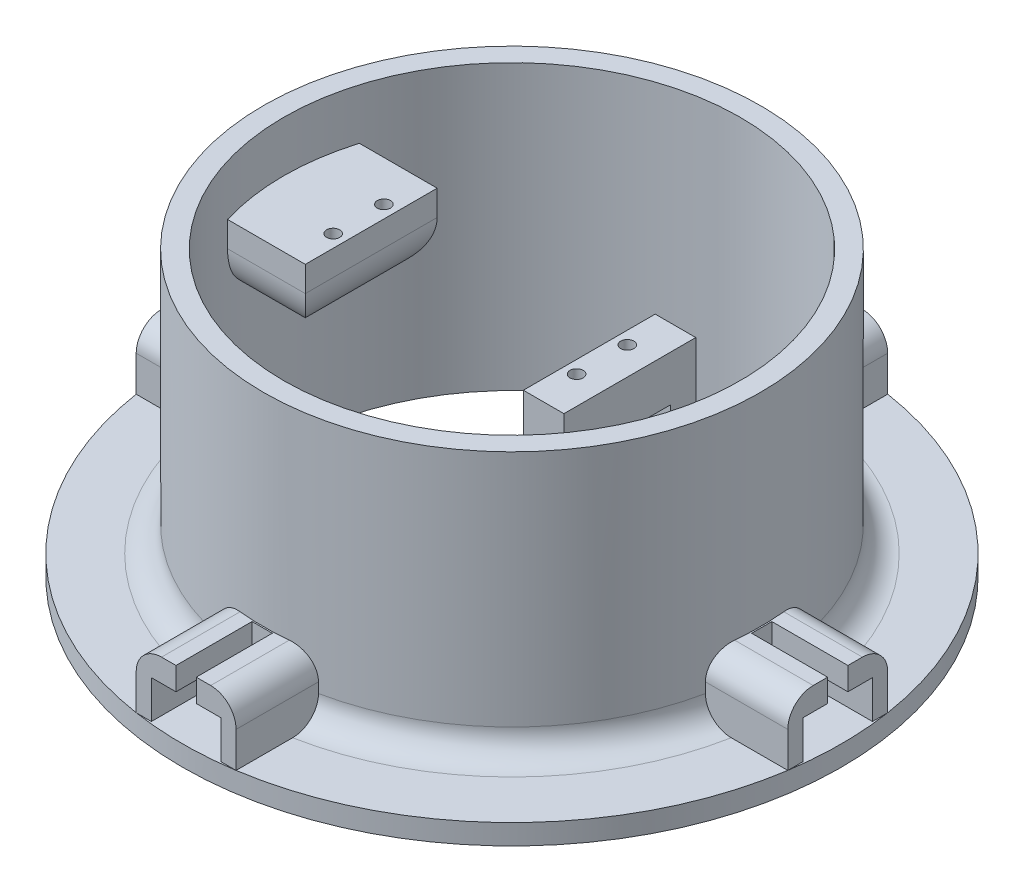
SolidWorks part; units mm, degrees
ref_plane "Alzado" through (0, 0, 0) normal (0, 0, 1) x (1, 0, 0)
ref_plane "Planta" through (0, 0, 0) normal (0, 1, 0) x (1, 0, 0)
ref_plane "Vista lateral" through (0, 0, 0) normal (1, 0, 0) x (0, 0, -1)
sketch "Croquis1" plane through (0, 0, 0) normal (0, 1, 0) x (1, 0, 0)
  circle A0 centre (0, 0) radius 45
  circle A1 centre (0, 0) radius 49
  dimension "D1" = 98
  dimension "D2" = 90
extrude "Saliente-Extruir1" add sketch "Croquis1" along normal blind 56
sketch "Croquis3" plane through (0, 0, 0) normal (0, 1, 0) x (1, 0, 0)
  circle A0 centre (0, 0) radius 49
  circle A1 centre (0, 0) radius 65
  dimension "D1" = 98
  dimension "D2" = 130
extrude "Saliente-Extruir2" add sketch "Croquis3" along normal blind 4
fillet "Redondeo1" radius 5 1 edges at (0, 4, 49)
sketch "Croquis4" plane through (0, 0, 0) normal (0, 1, 0) x (1, 0, 0)
  line L0 (45, 0) -> (19.25, 0) construction
  line L2 (15.25, -13) -> (23.25, -13)
  line L3 (15.25, -13) -> (15.25, 13)
  line L4 (15.25, 13) -> (23.25, 13)
  line L5 (23.25, -13) -> (23.25, 13)
  line L6 (15.25, -13) -> (23.25, 13) construction
  line L7 (15.25, 13) -> (23.25, -13) construction
  circle A0 centre (0, 0) radius 45 construction
  dimension "D1" = 25.75
  dimension "D2" = 8
  dimension "D3" = 26
extrude "Saliente-Extruir3" add sketch "Croquis4" along normal blind 46 separate body
sketch "Croquis5" plane through (0, 0, 0) normal (0, 1, 0) x (1, 0, 0)
  line L0 (15.25, 13) -> (32.7495, 30.8621)
  line L1 (0, 0) -> (45, 0) construction
  line L2 (38.8166, 22.7655) -> (27.25, 10.9592)
  line L3 (27.25, 10.9592) -> (27.25, -10.9592)
  line L4 (23.25, -13) -> (23.25, 13) construction
  line L5 (15.25, -13) -> (32.7495, -30.8621)
  line L6 (38.8166, -22.7655) -> (27.25, -10.9592)
  line L7 (15.25, -13) -> (23.25, -13) construction
  line L8 (23.25, 13) -> (15.25, 13) construction
  line L9 (15.25, -13) -> (23.25, -13)
  line L10 (23.25, -13) -> (23.25, 13)
  line L11 (23.25, 13) -> (15.25, 13)
  circle A0 centre (0, 0) radius 45 construction
  arc A1 (32.7495, -30.8621) -> (38.8166, -22.7655) centre (0, 0) ccw
  arc A2 (38.8166, 22.7655) -> (32.7495, 30.8621) centre (0, 0) ccw
  point P17 (27.25, 0)
  dimension "D1" = 4
  dimension "D2" = 10
extrude "Saliente-Extruir4" add sketch "Croquis5" along normal blind 2.2
sketch "Croquis6" plane through (0, 46, 0) normal (0, 1, 0) x (1, 0, 0)
  line L0 (15.25, 13) -> (-27.75, 13) construction
  line L1 (-27.75, 13) -> (-27.75, 0) construction
  line L2 (-27.75, 0) -> (-30.25, 0) construction
  line L3 (-30.25, 0) -> (-30.25, 5) construction
  line L5 (-27.75, 13) -> (-43.0813, 13)
  line L6 (-27.75, 13) -> (-27.75, -13)
  line L7 (-27.75, -13) -> (-43.0813, -13)
  circle A0 centre (0, 0) radius 45 construction
  arc A1 (-43.0813, 13) -> (-43.0813, -13) centre (0, 0) ccw
  dimension "D1" = 43
  dimension "D2" = 2.5
  dimension "D3" = 5
  dimension "D4" = 26
extrude "Saliente-Extruir5" add sketch "Croquis6" against normal blind 15
fillet "Redondeo2" radius 10 3 edges at (-35.4157, 31, -13) (-35.4157, 31, 13) (-27.75, 31, 0)
sketch "Croquis7" plane through (0, 46, 0) normal (0, 1, 0) x (1, 0, 0)
  line L0 (17.75, 0) -> (17.75, 5) construction
  line L2 (17.75, 0) -> (15.25, 0) construction
  line L3 (15.25, 13) -> (15.25, -13) construction
  line L4 (15.25, 0) -> (-30.25, 0) construction
  line L5 (-27.75, -13) -> (-27.75, 13) construction
  line L6 (-30.25, 0) -> (-30.25, -2.7854) construction
  line L7 (-30.25, -2.7854) -> (17.75, -2.7854) construction
  line L8 (-6.25, -2.7854) -> (-6.25, 3.2559) construction
  circle A0 centre (17.75, 5) radius 1.3
  circle A1 centre (17.75, -5) radius 1.3
  circle A2 centre (-30.25, -5) radius 1.3
  circle A3 centre (-30.25, 5) radius 1.3
  dimension "D4" = 2.6
  dimension "D1" = 2.5
  dimension "D2" = 2.5
  dimension "D3" = 5
  dimension "D5" = 5
extrude "Cortar-Extruir1" cut sketch "Croquis7" against normal blind 7.2
ref_plane "Plano1" through (15.25, 0, 0) normal (-1, 0, 0) x (0, 0, 1)
sketch "Croquis8" plane through (15.25, 0, 0) normal (-1, 0, 0) x (0, 0, 1)
  line L0 (0, 46) -> (0, 36) construction
  line L1 (-13, 46) -> (13, 46) construction
  line L2 (0, 36) -> (0, 4) construction
  line L3 (-13, 0) -> (13, 0) construction
  line L4 (13, 46) -> (13, 2.2) construction
  line L5 (-8, 3) -> (8, 3)
  line L6 (-8, 3) -> (-8, 37)
  line L7 (-8, 37) -> (8, 37)
  line L8 (8, 3) -> (8, 37)
  line L9 (-8, 3) -> (8, 37) construction
  line L10 (-8, 37) -> (8, 3) construction
  point P8 (0, 20)
  dimension "D1" = 10
  dimension "D2" = 4
  dimension "D3" = 5
  dimension "D4" = 9
extrude "Cortar-Extruir2" cut sketch "Croquis8" against normal up to next
sketch "Croquis9" plane through (0, 4, 0) normal (0, 1, 0) x (1, 0, 0)
  line L0 (-48, 0) -> (-65, 0) construction
  line L1 (-48, 0) -> (-48, -9.8489) construction
  line L3 (-48, -9.8489) -> (-64.2495, -9.8489)
  line L4 (-48, -9.8489) -> (-48, 9.8489)
  line L5 (-48, 9.8489) -> (-64.2495, 9.8489)
  line L6 (-64.2495, -9.8489) -> (-64.2495, 9.8489)
  circle A0 centre (0, 0) radius 65 construction
  circle A1 centre (0, 0) radius 49 construction
  circle A2 centre (0, 0) radius 49 construction
  circle A3 centre (0, 0) radius 49 construction
  dimension "D1" = 48
extrude "Saliente-Extruir6" add sketch "Croquis9" along normal blind 12
fillet "Redondeo3" radius 5 2 edges at (-56.1248, 16, -9.8489) (-56.1248, 16, 9.8489)
sketch "Croquis11" plane through (-64.2495, 0, 0) normal (-1, 0, 0) x (0, 0, 1)
  line L0 (0, 4) -> (0, 16) construction
  line L1 (-9.8489, 4) -> (9.8489, 4) construction
  line L2 (-4.8489, 16) -> (4.8489, 16) construction
  line L3 (6.8489, 4) -> (6.8489, 16) construction
  line L4 (9.8489, 11) -> (9.8489, 4) construction
  line L5 (-9.8489, 11) -> (-9.8489, 4) construction
  line L6 (6.8489, 4) -> (-6.8489, 4)
  line L7 (6.8489, 4) -> (6.8489, 11.5)
  line L8 (6.8489, 11.5) -> (-6.8489, 11.5)
  line L9 (-6.8489, 4) -> (-6.8489, 11.5)
  dimension "D1" = 3
  dimension "D2" = 12
  dimension "D3" = 7.5
  dimension "D4" = 3
extrude "Cortar-Extruir3" cut sketch "Croquis11" against normal blind 12
sketch "Croquis12" plane through (-64.2495, 0, 0) normal (-1, 0, 0) x (0, 0, 1)
  line L0 (0, 16) -> (0, 11.5) construction
  line L1 (4.8489, 16) -> (-4.8489, 16) construction
  line L2 (6.8489, 11.5) -> (-6.8489, 11.5) construction
  line L3 (-4.8489, 16) -> (4.8489, 16) construction
  line L4 (-2, 11.5) -> (2, 11.5)
  line L5 (-2, 11.5) -> (-2, 16)
  line L6 (-2, 16) -> (2, 16)
  line L7 (2, 11.5) -> (2, 16)
  line L8 (-2, 11.5) -> (2, 16) construction
  line L9 (-2, 16) -> (2, 11.5) construction
  point P6 (0, 13.75)
  dimension "D1" = 4
extrude "Cortar-Extruir4" cut sketch "Croquis12" against normal blind 15
pattern_circular "MatrizC1" count 4 over 360 about axis through (0, 0, 0) along (0, 1, 0) of "Saliente-Extruir6", "Redondeo3", "Cortar-Extruir4", "Cortar-Extruir3"
